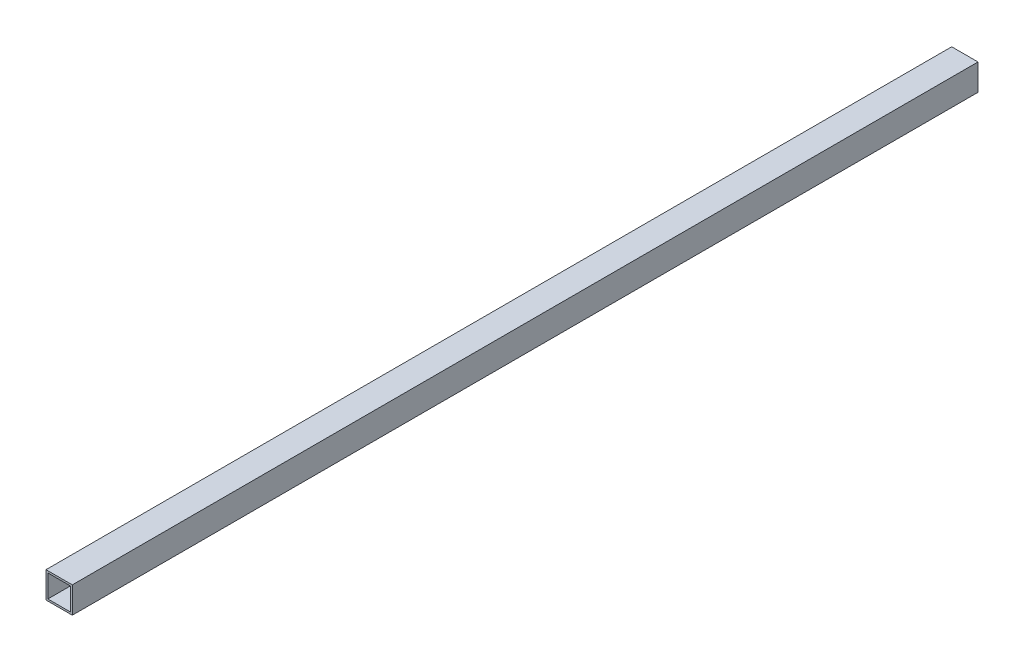
SolidWorks part; units mm, degrees
ref_plane "Front Plane" through (0, 0, 0) normal (0, 0, 1) x (1, 0, 0)
ref_plane "Top Plane" through (0, 0, 0) normal (0, 1, 0) x (1, 0, 0)
ref_plane "Right Plane" through (0, 0, 0) normal (1, 0, 0) x (0, 0, -1)
sketch "Sketch2" plane through (0, 0, 0) normal (0, 0, 1) x (1, 0, 0)
  line L1 (-22.225, -22.225) -> (22.225, -22.225)
  line L2 (-22.225, -22.225) -> (-22.225, 22.225)
  line L3 (-22.225, 22.225) -> (22.225, 22.225)
  line L4 (22.225, -22.225) -> (22.225, 22.225)
  line L5 (-22.225, -22.225) -> (22.225, 22.225) construction
  line L6 (-22.225, 22.225) -> (22.225, -22.225) construction
  line L7 (-19.05, -19.05) -> (19.05, -19.05)
  line L8 (-19.05, -19.05) -> (-19.05, 19.05)
  line L9 (-19.05, 19.05) -> (19.05, 19.05)
  line L10 (19.05, -19.05) -> (19.05, 19.05)
  line L11 (-19.05, -19.05) -> (19.05, 19.05) construction
  line L12 (-19.05, 19.05) -> (19.05, -19.05) construction
  point P0 (0, 0)
  point P6 (0, 0)
  dimension "D1" = 44.45
  dimension "D2" = 3.175
extrude "Boss-Extrude1" add sketch "Sketch2" against normal blind 1530.35
